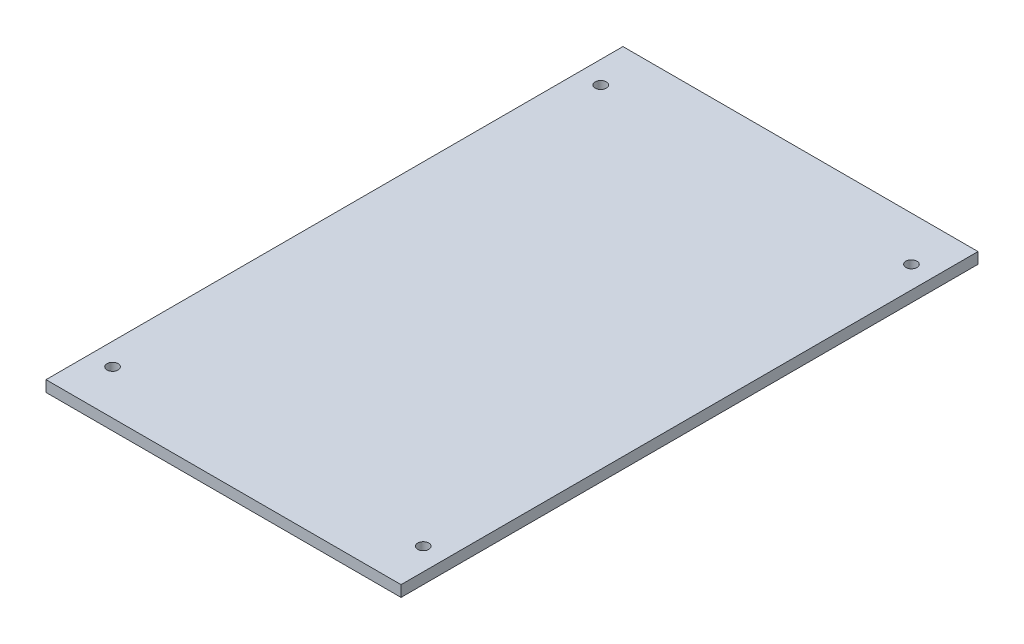
SolidWorks part; units mm, degrees
material "Balsa"
ref_plane "Front Plane" through (0, 0, 0) normal (0, 0, 1) x (1, 0, 0)
ref_plane "Top Plane" through (0, 0, 0) normal (0, 1, 0) x (1, 0, 0)
ref_plane "Right Plane" through (0, 0, 0) normal (1, 0, 0) x (0, 0, -1)
sketch "Sketch1" plane through (0, 0, 0) normal (0, 1, 0) x (1, 0, 0)
  line L1 (-101.6, 165.1) -> (101.6, 165.1)
  line L2 (-101.6, 165.1) -> (-101.6, -165.1)
  line L3 (-101.6, -165.1) -> (101.6, -165.1)
  line L4 (101.6, 165.1) -> (101.6, -165.1)
  line L5 (-101.6, 165.1) -> (101.6, -165.1) construction
  line L6 (-101.6, -165.1) -> (101.6, 165.1) construction
  point P0 (0, 0)
  dimension "D1" = 330.2
  dimension "D2" = 203.2
extrude "Boss-Extrude1" add sketch "Sketch1" along normal blind 6.35
sketch "Sketch2" plane through (0, 6.35, 0) normal (0, 1, 0) x (1, 0, 0)
  line L0 (101.6, -165.1) -> (101.6, 165.1) construction
  line L1 (-88.9, 139.7) -> (88.9, 139.7) construction
  line L2 (-88.9, 139.7) -> (-88.9, -139.7) construction
  line L3 (-88.9, -139.7) -> (88.9, -139.7) construction
  line L4 (88.9, 139.7) -> (88.9, -139.7) construction
  line L5 (-88.9, 139.7) -> (88.9, -139.7) construction
  line L6 (-88.9, -139.7) -> (88.9, 139.7) construction
  line L7 (-101.6, -165.1) -> (101.6, -165.1) construction
  circle A0 centre (88.9, 139.7) radius 3.175
  circle A1 centre (-88.9, 139.7) radius 3.175
  circle A2 centre (88.9, -139.7) radius 3.175
  circle A3 centre (-88.9, -139.7) radius 3.175
  point P0 (0, 0)
  dimension "D1" = 6.35
  dimension "D2" = 12.7
  dimension "D3" = 25.4
extrude "Cut-Extrude1" cut sketch "Sketch2" against normal through all both and the other way through all
